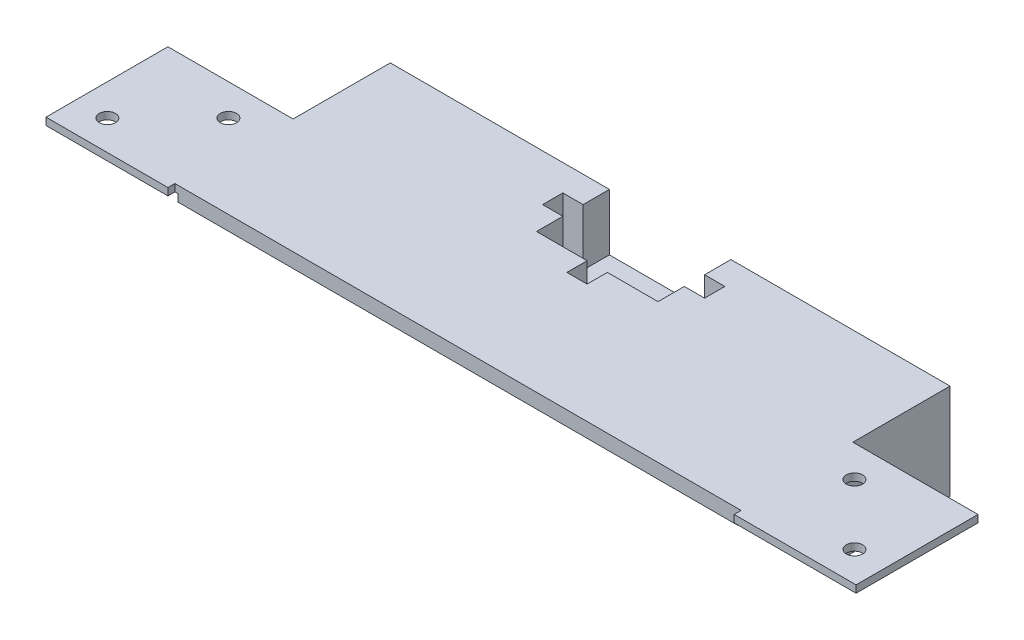
SolidWorks part; units mm, degrees
ref_plane "Alzado" through (0, 0, 0) normal (0, 0, 1) x (1, 0, 0)
ref_plane "Planta" through (0, 0, 0) normal (0, 1, 0) x (1, 0, 0)
ref_plane "Vista lateral" through (0, 0, 0) normal (1, 0, 0) x (0, 0, -1)
sketch "Croquis1" plane through (0, 0, 0) normal (0, 1, 0) x (1, 0, 0)
  line L0 (0, 16.8548) -> (0, -58.7896) construction
  line L1 (-69.5, -36.2916) -> (-69.5, -34.5716) construction
  line L2 (-100, -36.2916) -> (-69.5, -36.2916) construction
  line L3 (-100, -5.7916) -> (-100, -36.2916) construction
  line L4 (-69.5, -5.7916) -> (-100, -5.7916) construction
  line L5 (-69.5, -34.5716) -> (-69.5, -5.7916) construction
  line L17 (-69.5, -9.7916) -> (69.5, -9.7916) construction
  line L18 (69.5, -34.5716) -> (69.5, -5.7916) construction
  line L19 (69.5, -5.7916) -> (100, -5.7916) construction
  line L20 (100, -5.7916) -> (100, -36.2916) construction
  line L21 (100, -36.2916) -> (69.5, -36.2916) construction
  line L22 (69.5, -36.2916) -> (69.5, -34.5716) construction
  line L23 (69.5, -34.5716) -> (-69.5, -34.5716) construction
  circle A0 centre (-77.2782, -13.5698) radius 2 construction
  circle A1 centre (-92.2218, -28.5135) radius 2 construction
  circle A2 centre (-56.5, -26.2016) radius 2 construction
  circle A11 centre (56.5, -26.2016) radius 2 construction
  circle A12 centre (92.2218, -28.5135) radius 2 construction
  circle A13 centre (77.2782, -13.5698) radius 2 construction
  point P23 (0, -34.5716)
  point P28 (0, -9.7916)
sketch "Croquis4" plane through (0, 0, 0) normal (0, 1, 0) x (1, 0, 0)
  line L0 (69.5, -34.5716) -> (-69.5, -34.5716) construction
  line L1 (100, -36.2916) -> (69.5, -36.2916) construction
  line L2 (100, -5.7916) -> (100, -36.2916) construction
  line L3 (69.5, -5.7916) -> (100, -5.7916) construction
  line L5 (-69.5, -9.7916) -> (69.5, -9.7916) construction
  line L6 (0, 16.8548) -> (0, -58.7896) construction
  line L7 (69.5, -34.5716) -> (0, -34.5716) construction
  line L8 (100, -36.2916) -> (69.5, -36.2916) construction
  line L9 (100, -5.7916) -> (100, -36.2916) construction
  line L10 (69.5, -5.7916) -> (100, -5.7916) construction
  line L12 (0, -9.7916) -> (69.5, -9.7916) construction
  line L13 (0, 16.8548) -> (0, -58.7896) construction
  line L15 (69.5, -36.2916) -> (69.5, -34.5716) construction
  line L16 (69.5, -36.2916) -> (69.5, -34.5716) construction
  line L17 (100, -35.8916) -> (69.9, -35.8916)
  line L18 (69.9, -35.8916) -> (69.9, -34.1716)
  line L19 (69.9, -34.1716) -> (0, -34.1716)
  line L20 (100, -35.8916) -> (100, -5.7916)
  line L22 (100, -5.7916) -> (-100, -5.7916)
  line L23 (-69.9, -34.1716) -> (0, -34.1716)
  line L24 (-69.9, -35.8916) -> (-69.9, -34.1716)
  line L25 (-100, -35.8916) -> (-69.9, -35.8916)
  line L26 (-100, -35.8916) -> (-100, -5.7916)
  point P21 (0, -5.7916)
  dimension "D1" = 0.4
extrude "Saliente-Extruir1" add sketch "Croquis4" along normal blind 1.8
sketch "Croquis5" plane through (0, 1.8, 0) normal (0, 1, 0) x (1, 0, 0)
  line L0 (69.5, -34.5716) -> (-69.5, -34.5716) construction
  line L1 (69.5, -34.5716) -> (69.5, -5.7916) construction
  line L2 (-69.5, -9.7916) -> (69.5, -9.7916) construction
  line L3 (0, 16.8548) -> (0, -58.7896) construction
  line L4 (69.5, -34.5716) -> (0, -34.5716) construction
  line L5 (69.5, -34.5716) -> (69.5, -9.7916) construction
  line L6 (0, -9.7916) -> (69.5, -9.7916) construction
  line L7 (0, 16.8548) -> (0, -58.7896) construction
  line L11 (-69.1, -34.1716) -> (69.1, -34.1716)
  line L17 (-69.9, -34.1716) -> (69.9, -34.1716) construction
  line L18 (69.1, -34.1716) -> (69.1, -9.7916)
  line L19 (69.1, -34.5716) -> (69.1, -9.7916) construction
  line L20 (69.1, -9.7916) -> (69.1, -5.7916)
  line L21 (100, -5.7916) -> (-100, -5.7916) construction
  line L22 (69.1, -5.7916) -> (-69.1, -5.7916)
  line L23 (-69.1, -34.1716) -> (-69.1, -9.7916)
  line L24 (-69.1, -9.7916) -> (-69.1, -5.7916)
  point P20 (0, -10.2916)
  point P21 (0, -34.1716)
  point P23 (0, -5.7916)
  dimension "D1" = 0.4
extrude "Saliente-Extruir2" add sketch "Croquis5" against normal blind 1.8 from surface at -1.8 starting at face at (0, 0, 27.9366)
sketch "Croquis6" plane through (0, 1.8, 0) normal (0, 1, 0) x (1, 0, 0)
  line L0 (-69.5, -9.7916) -> (69.5, -9.7916) construction
  line L1 (0, -9.7916) -> (69.5, -9.7916) construction
  line L2 (0, 16.8548) -> (0, -58.7896) construction
  line L3 (0, 16.8548) -> (0, -58.7896) construction
  line L4 (69.5, -34.5716) -> (69.5, -5.7916) construction
  line L5 (69.5, -9.7916) -> (69.5, -5.7916) construction
  line L14 (-69.1, -9.1916) -> (69.1, -9.1916)
  line L15 (69.1, -9.1916) -> (69.1, -5.7916)
  line L16 (69.1, -9.7916) -> (69.1, -5.7916) construction
  line L17 (0, -9.1916) -> (69.5, -9.1916) construction
  line L18 (69.1, -5.7916) -> (-69.1, -5.7916)
  line L19 (100, -5.7916) -> (-100, -5.7916) construction
  line L20 (-69.1, -9.1916) -> (-69.1, -5.7916)
  point P17 (0, -5.7916)
  dimension "D1" = 0.6
  dimension "D2" = 0.4
extrude "Saliente-Extruir3" add sketch "Croquis6" against normal blind 20 from surface at -3.6 starting at face at (0, -1.8, 19.9816)
sketch "Croquis7" plane through (0, 0, 5.7916) normal (0, 0, -1) x (-1, 0, 0)
  line L0 (0, 22.365) -> (0, -38.5622) construction
  line L1 (0, 1.8) -> (75, 1.8)
  line L2 (-100, 1.8) -> (100, 1.8) construction
  line L3 (75, 1.8) -> (75, -21.8)
  line L4 (-69.1, -21.8) -> (69.1, -21.8) construction
  line L5 (75, -21.8) -> (0, -21.8)
  dimension "D1" = 75
sketch "Croquis8" plane through (0, 0, 5.7916) normal (0, 0, -1) x (-1, 0, 0)
  line L0 (0, 22.365) -> (0, -38.5622) construction
  line L1 (0, 22.365) -> (0, -38.5622) construction
  line L2 (-69.1, 1.8) -> (69.1, 1.8)
  line L3 (0, 1.8) -> (75, 1.8) construction
  line L4 (69.1, 1.8) -> (69.1, -21.8)
  line L5 (69.1, -21.8) -> (-69.1, -21.8)
  line L6 (-69.1, 1.8) -> (-69.1, -21.8)
  point P12 (0, 1.8)
  point P13 (0, -21.8)
extrude "Saliente-Extruir4" add sketch "Croquis8" along normal blind 24
sketch "Croquis9" plane through (0, 1.8, 0) normal (0, 1, 0) x (1, 0, 0)
  line L0 (0, 16.8548) -> (0, -58.7896) construction
  line L1 (0, 33.1742) -> (0, -58.7896) construction
  line L2 (15, 18.2084) -> (-15, 18.2084)
  line L3 (-69.1, 18.2084) -> (69.1, 18.2084) construction
  line L4 (-15, 18.2084) -> (-15, 0.2084)
  line L5 (-15, 0.2084) -> (15, 0.2084)
  line L6 (15, 18.2084) -> (15, 0.2084)
  point P10 (0, 0.2084)
  point P11 (0, 18.2084)
  dimension "D1" = 18
  dimension "D2" = 15
extrude "Cortar-Extruir1" cut sketch "Croquis9" against normal blind 14
sketch "Croquis10" plane through (0, -12.2, 0) normal (0, 1, 0) x (1, 0, 0)
  line L0 (0, 16.8548) -> (0, -58.7896) construction
  line L1 (0, 22.5663) -> (0, -58.7896) construction
  line L2 (15, 18.2084) -> (-15, 18.2084) construction
  line L3 (15, 18.2084) -> (-15, 18.2084) construction
  circle A0 centre (-4.75, 10.2084) radius 1
  circle A1 centre (4.75, 10.2084) radius 1
  dimension "D1" = 2
  dimension "D2" = 4.75
  dimension "D3" = 8
sketch "Croquis11" plane through (0, 1.8, 0) normal (0, 1, 0) x (1, 0, 0)
  circle A0 centre (92.2218, -28.5135) radius 2 construction
  circle A1 centre (77.2782, -13.5698) radius 2 construction
  circle A2 centre (-77.2782, -13.5698) radius 2 construction
  circle A3 centre (-92.2218, -28.5135) radius 2 construction
  circle A4 centre (92.2218, -28.5135) radius 2
  circle A5 centre (77.2782, -13.5698) radius 2
  circle A6 centre (-77.2782, -13.5698) radius 2
  circle A7 centre (-92.2218, -28.5135) radius 2
extrude "Cortar-Extruir2" cut sketch "Croquis11" against normal through all
sketch "Croquis12" plane through (0, -21.8, 0) normal (0, 1, 0) x (1, 0, 0)
  line L0 (-17.044, 0.2084) -> (17.044, 0.2084) construction
  text T0 "NUT BOT" font "Century Gothic" height 6
  point P7 (0, 0.2084)
extrude "Cortar-Extruir4" cut sketch "Croquis12" along normal blind 1
sketch "Croquis14" plane through (0, 1.8, 0) normal (0, 1, 0) x (1, 0, 0)
  line L0 (15, 0.2084) -> (15, 18.2084) construction
  line L1 (-15, 18.2084) -> (-15, 0.2084) construction
  line L2 (15, 0.2084) -> (15, 18.2084) construction
  line L3 (-15, 18.2084) -> (-15, 0.2084) construction
  line L4 (-18.7981, 9.2084) -> (18.7981, 9.2084) construction
  line L5 (0, 20.6624) -> (0, -12.0045) construction
  line L7 (20, 6.7084) -> (15, 6.7084)
  line L8 (-20, 11.7084) -> (-15, 11.7084)
  line L9 (-20, 11.7084) -> (-20, 6.7084)
  line L10 (-20, 6.7084) -> (-15, 6.7084)
  line L11 (-15, 11.7084) -> (-15, 6.7084)
  line L12 (-20, 11.7084) -> (-15, 6.7084) construction
  line L13 (-20, 6.7084) -> (-15, 11.7084) construction
  line L14 (15, 11.7084) -> (15, 6.7084)
  line L19 (-15, 0.2084) -> (15, 0.2084) construction
  line L20 (2.5, -4.7916) -> (-2.5, -4.7916)
  line L21 (2.5, -4.7916) -> (2.5, 0.2084)
  line L22 (2.5, 0.2084) -> (-2.5, 0.2084)
  line L23 (-2.5, -4.7916) -> (-2.5, 0.2084)
  line L24 (2.5, -4.7916) -> (-2.5, 0.2084) construction
  line L25 (2.5, 0.2084) -> (-2.5, -4.7916) construction
  line L26 (20, 11.7084) -> (15, 11.7084)
  line L27 (20, 11.7084) -> (20, 6.7084)
  point P6 (-15, 9.2084)
  point P13 (-17.5, 9.2084)
  point P22 (17.5, 9.2084)
  point P23 (0, -2.2916)
  dimension "D1" = 5
  dimension "D2" = 5
  dimension "D3" = 5
  dimension "D4" = 5
extrude "Cortar-Extruir5" cut sketch "Croquis14" against normal up to surface (14 mm away) up to face at (0, -12.2, -9.2084)
